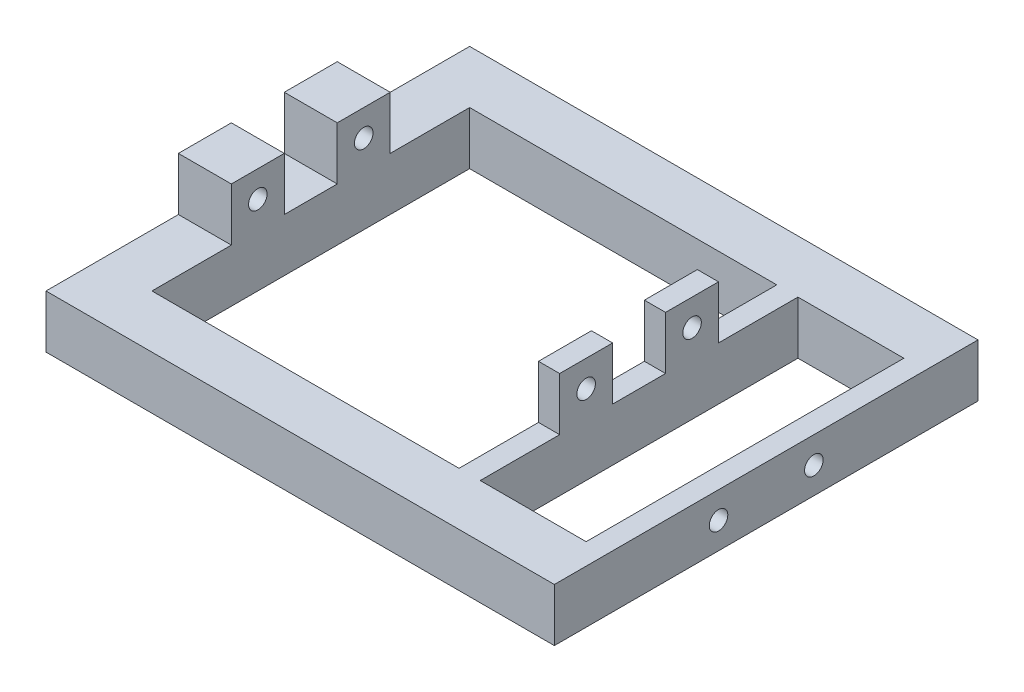
SolidWorks part; units mm, degrees
ref_plane "Front Plane" through (0, 0, 0) normal (0, 0, 1) x (1, 0, 0)
ref_plane "Top Plane" through (0, 0, 0) normal (0, 1, 0) x (1, 0, 0)
ref_plane "Right Plane" through (0, 0, 0) normal (1, 0, 0) x (0, 0, -1)
sketch "Sketch1" plane through (0, 0, 0) normal (0, 1, 0) x (1, 0, 0)
  line L2 (0, 0) -> (0, 80)
  line L12 (0, 80) -> (96, 80)
  line L13 (0, 0) -> (96, 0)
  line L15 (92, 70) -> (92, 10)
  line L16 (10, 70) -> (92, 70)
  line L17 (10, 70) -> (10, 10)
  line L18 (10, 10) -> (92, 10)
  line L20 (96, 80) -> (96, 0)
  dimension "D1" = 80
  dimension "D2" = 10
  dimension "D3" = 10
  dimension "D4" = 10
  dimension "D5" = 96
  dimension "D6" = 4
extrude "Boss-Extrude1" add sketch "Sketch1" along normal blind 10
sketch "Sketch5" plane through (0, 0, -70) normal (0, 0, 1) x (1, 0, 0)
  line L0 (92, 10) -> (10, 10) construction
  line L1 (68, 10) -> (72, 10)
  line L2 (68, 10) -> (68, 0)
  line L3 (68, 0) -> (72, 0)
  line L4 (72, 10) -> (72, 0)
  line L5 (92, 0) -> (10, 0) construction
  line L6 (92, 10) -> (92, 0) construction
  dimension "D1" = 20
  dimension "D2" = 4
extrude "Boss-Extrude2" add sketch "Sketch5" along normal up to next
sketch "Sketch6" plane through (0, 10, 0) normal (0, 1, 0) x (1, 0, 0)
  line L0 (10, 70) -> (10, 10) construction
  line L1 (72, 10) -> (72, 70) construction
  line L2 (68, 10) -> (68, 70) construction
  line L3 (10, 45) -> (0, 45)
  line L4 (68, 45) -> (72, 45)
  line L5 (68, 45) -> (68, 35)
  line L6 (68, 35) -> (72, 35)
  line L7 (72, 45) -> (72, 35)
  line L8 (10, 45) -> (10, 35)
  line L9 (10, 35) -> (0, 35)
  line L10 (0, 45) -> (0, 35)
  line L11 (0, 80) -> (0, 0) construction
  line L12 (96, 80) -> (0, 80) construction
  line L13 (0, 45) -> (10, 45)
  line L14 (0, 45) -> (0, 55)
  line L15 (0, 55) -> (10, 55)
  line L16 (10, 45) -> (10, 55)
  line L17 (0, 35) -> (10, 35)
  line L18 (0, 35) -> (0, 25)
  line L19 (0, 25) -> (10, 25)
  line L20 (10, 35) -> (10, 25)
  line L21 (68, 45) -> (72, 45)
  line L22 (68, 45) -> (68, 55)
  line L23 (68, 55) -> (72, 55)
  line L24 (72, 45) -> (72, 55)
  line L25 (68, 35) -> (72, 35)
  line L26 (68, 35) -> (68, 25)
  line L27 (68, 25) -> (72, 25)
  line L28 (72, 35) -> (72, 25)
  line M7 (72, 10) -> (72, 70)
  line M13 (0, 80) -> (0, 0)
  line M20 (68, 70) -> (68, 10)
  line M22 (10, 10) -> (10, 70)
  dimension "D1" = 10
  dimension "D2" = 10
  dimension "D3" = 10
  dimension "D4" = 10
  dimension "D5" = 10
  dimension "D6" = 25
  dimension "D7" = 25
extrude "Boss-Extrude3" add sketch "Sketch6" along normal blind 10 contours L15 L3 M13 M22 | L19 L9 M13 M22 | L23 L4 M20 M7 | L27 L6 M20 M7
sketch "Sketch7" plane through (72, 0, 0) normal (1, 0, 0) x (0, 0, -1)
  line L2 (25, 20) -> (35, 20) construction
  line L3 (35, 20) -> (35, 10) construction
  line L4 (45, 20) -> (55, 20) construction
  line L5 (55, 20) -> (55, 10) construction
  circle A1 centre (30, 15) radius 1.75
  circle A2 centre (50, 15) radius 1.75
  dimension "D4" = 3.5
  dimension "D5" = 3.5
  dimension "D6" = 5
  dimension "D7" = 5
  dimension "D8" = 5
  dimension "D9" = 5
extrude "Cut-Extrude3" cut sketch "Sketch7" against normal through all
sketch "Sketch10" plane through (96, 0, 0) normal (1, 0, 0) x (0, 0, -1)
  line L0 (40, 10) -> (40, 0)
  line L1 (0, 10) -> (80, 10) construction
  line L2 (0, 0) -> (80, 0) construction
  circle A0 centre (31, 5) radius 1.75
  circle A1 centre (49, 5) radius 1.75
  dimension "D1" = 9
  dimension "D2" = 9
  dimension "D3" = 3.5
  dimension "D4" = 3.5
extrude "Cut-Extrude4" cut sketch "Sketch10" against normal up to next contours A0 | A1
